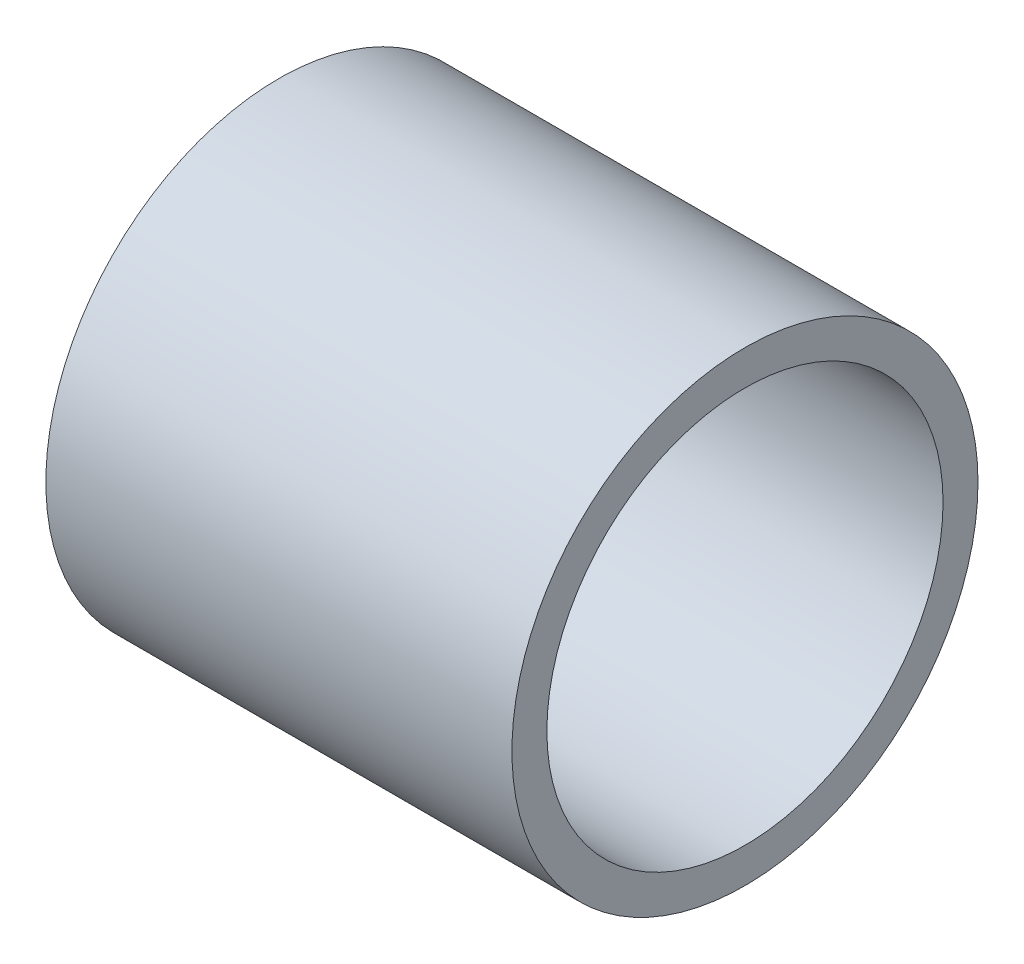
SolidWorks part; units mm, degrees
ref_plane "前视基准面" through (0, 0, 0) normal (0, 0, 1) x (1, 0, 0)
ref_plane "上视基准面" through (0, 0, 0) normal (0, 1, 0) x (1, 0, 0)
ref_plane "右视基准面" through (0, 0, 0) normal (1, 0, 0) x (0, 0, -1)
sketch "草图1" plane through (0, 0, 0) normal (1, 0, 0) x (0, 0, -1)
  circle A0 centre (0, 0) radius 10
  circle A1 centre (0, 0) radius 8.5
  dimension "D1" = 20
  dimension "D2" = 17
extrude "凸台-拉伸1" add sketch "草图1" along normal blind 20
